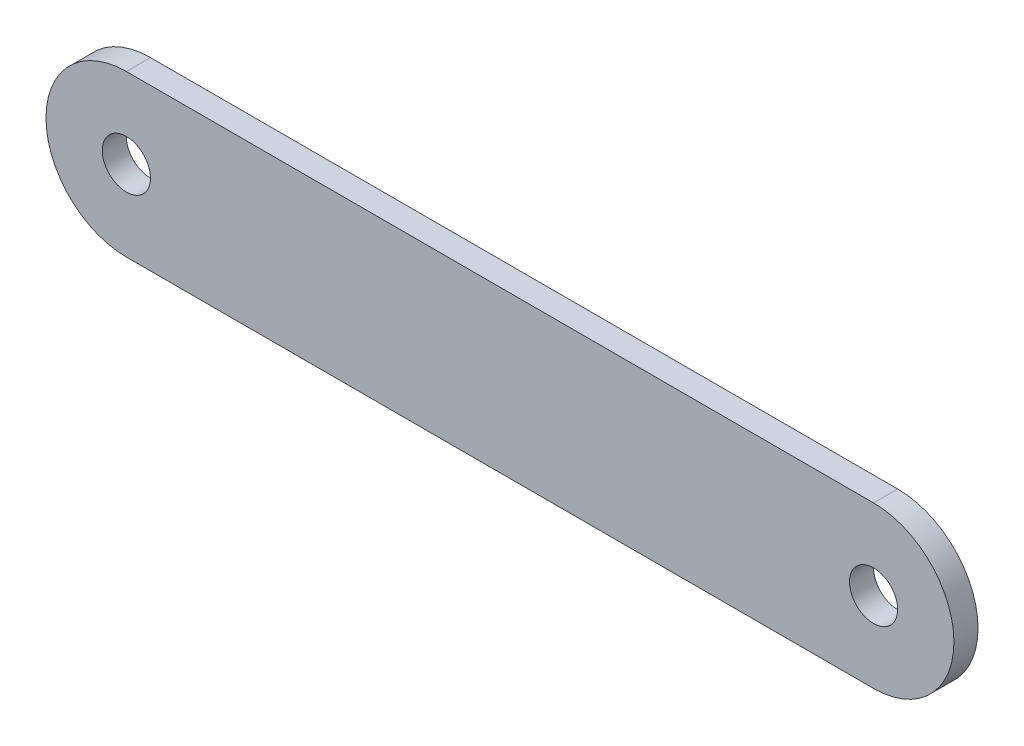
SolidWorks part; units mm, degrees
material "3.3535 (EN-AW 5754)"
ref_plane "Front" through (0, 0, 0) normal (0, 0, 1) x (1, 0, 0)
ref_plane "Top" through (0, 0, 0) normal (0, 1, 0) x (1, 0, 0)
ref_plane "Right" through (0, 0, 0) normal (1, 0, 0) x (0, 0, -1)
sketch "Esquisse1" plane through (0, 0, 0) normal (0, 0, 1) x (1, 0, 0)
  line L0 (0, 5) -> (46.5, 5)
  line L1 (46.5, -5) -> (0, -5)
  circle A0 centre (0, 0) radius 1.5
  circle A1 centre (46.5, 0) radius 1.5
  arc A2 (46.5, 5) -> (46.5, -5) centre (46.5, 0) cw
  arc A3 (0, -5) -> (0, 5) centre (0, 0) cw
  dimension "D1" = 3
  dimension "D2" = 10
  dimension "D3" = 46.5
extrude "Boss.-Extru.1" add sketch "Esquisse1" along normal blind 1.5
